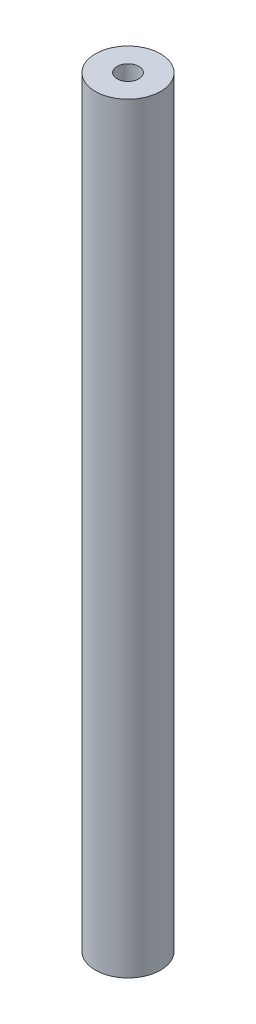
SolidWorks part; units mm, degrees
ref_plane "Alzado" through (0, 0, 0) normal (0, 0, 1) x (1, 0, 0)
ref_plane "Planta" through (0, 0, 0) normal (0, 1, 0) x (1, 0, 0)
ref_plane "Vista lateral" through (0, 0, 0) normal (1, 0, 0) x (0, 0, -1)
sketch "Croquis3" plane through (0, 0, 0) normal (0, 1, 0) x (1, 0, 0)
  circle A0 centre (0, 8.2856) radius 3
  circle A1 centre (0, 8.2856) radius 1
  dimension "D1" = 6
  dimension "D2" = 2
extrude "Saliente-Extruir2" add sketch "Croquis3" along normal blind 70
